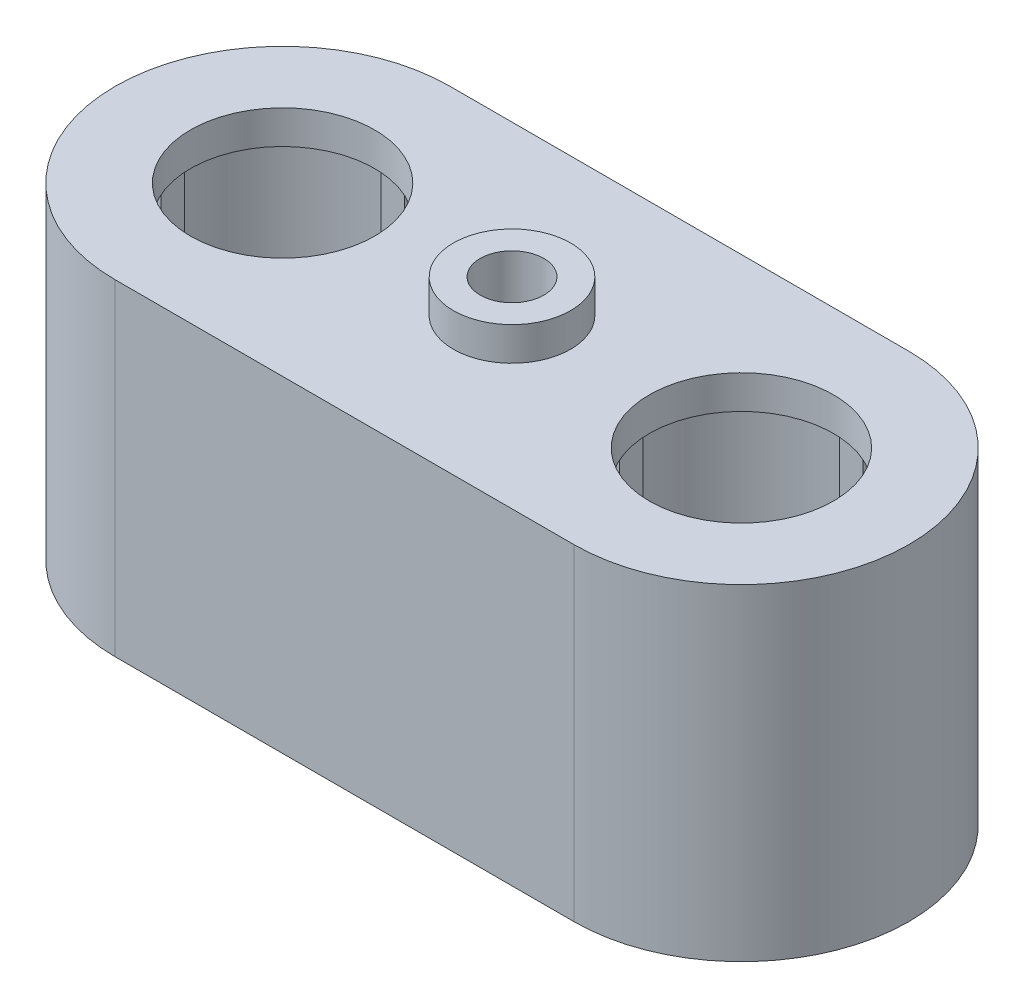
SolidWorks part; units mm, degrees
ref_plane "Front Plane" through (0, 0, 0) normal (0, 0, 1) x (1, 0, 0)
ref_plane "Top Plane" through (0, 0, 0) normal (0, 1, 0) x (1, 0, 0)
ref_plane "Right Plane" through (0, 0, 0) normal (1, 0, 0) x (0, 0, -1)
sketch "Sketch1" plane through (0, 0, 0) normal (0, 1, 0) x (1, 0, 0)
  line L3 (2.25, 5) -> (-2.25, 5)
  line L6 (2.35, -5) -> (-2.35, -5)
  line L16 (-1043.8651, 0) -> (-45, 0) construction
  line L17 (-2.25, 5) -> (-6.85, 5)
  line L18 (2.25, 5) -> (6.85, 5)
  line L19 (-2.35, -5) -> (-6.85, -5)
  line L20 (2.35, -5) -> (6.85, -5)
  line L21 (0, 0) -> (0, -10) construction
  line L28 (-1.85, 0) -> (1.85, 0) construction
  line L29 (45, 0) -> (1043.8651, 0) construction
  circle A0 centre (0, 0) radius 45 construction
  circle A18 centre (0, 0) radius 0.95
  arc A23 (-6.85, -5) -> (-6.85, 5) centre (-6.85, 0) ccw construction
  arc A28 (6.85, 5) -> (6.85, -5) centre (6.85, 0) ccw construction
  arc A30 (6.85, 5) -> (6.85, -5) centre (6.85, 0) ccw
  arc A31 (-6.85, -5) -> (-6.85, 5) centre (-6.85, 0) ccw
  dimension "D1" = 90
  dimension "D2" = 6.85
  dimension "D5" = 10
  dimension "D9" = 1.9
  dimension "D7" = 10
  dimension "D6" = 6.85
extrude "Boss-Extrude1" add sketch "Sketch1" along normal blind 2.5
sketch "Sketch2" plane through (0, 0, 0) normal (0, 1, 0) x (1, 0, 0)
  line L0 (0, 0) -> (-6.85, 0) construction
  line L1 (-13.4792, 0.75) -> (-11.7934, 0.75)
  line L2 (-13.4792, -0.75) -> (-11.7934, -0.75)
  line L3 (-12.5007, -0.75) -> (-12.5007, 0.75) construction
  line L4 (-17.25, 0) -> (0.95, 0) construction
  line L5 (-7.2, 3.9847) -> (-7.2, 3.2847)
  line L6 (-6.5, 3.9847) -> (-6.5, 3.2847)
  line L7 (-6.85, 0) -> (-6.85, 4) construction
  line L9 (-7.2, 3.2847) -> (-6.5, 3.2847)
  line L10 (-3.5653, 0.35) -> (-3.5653, -0.35)
  line L11 (-2.8653, 0.35) -> (-3.5653, 0.35)
  line L12 (-2.8653, -0.35) -> (-3.5653, -0.35)
  line L13 (-6.5, -3.2847) -> (-7.2, -3.2847)
  line L14 (-6.5, -3.9847) -> (-6.5, -3.2847)
  line L15 (-7.2, -3.9847) -> (-7.2, -3.2847)
  line L16 (-10.1347, -0.35) -> (-10.1347, 0.35)
  line L17 (-10.8347, -0.35) -> (-10.1347, -0.35)
  line L18 (-10.8347, 0.35) -> (-10.1347, 0.35)
  line L42 (-6.85, 5) -> (6.85, 5)
  line L43 (-6.85, -5) -> (6.85, -5)
  line L44 (-3.85, 4) -> (3.85, 4)
  line L45 (-7.2, 3.9847) -> (-6.5, 3.9847) construction
  line L46 (-3.85, -4) -> (3.85, -4)
  line L47 (-6.85, -4) -> (6.75, -4) construction
  line L48 (6.5, 3.9847) -> (6.5, 3.2847)
  line L49 (6.5, 3.2847) -> (7.2, 3.2847)
  line L50 (7.2, 3.9847) -> (7.2, 3.2847)
  line L51 (10.8347, 0.35) -> (10.1347, 0.35)
  line L52 (11.75, 0) -> (16.25, 0) construction
  line L53 (10.1347, 0.35) -> (10.1347, -0.35)
  line L54 (10.8347, -0.35) -> (10.1347, -0.35)
  line L55 (7.2, -3.9847) -> (7.2, -3.2847)
  line L56 (7.2, -3.2847) -> (6.5, -3.2847)
  line L57 (6.5, -3.9847) -> (6.5, -3.2847)
  line L58 (2.8653, -0.35) -> (3.5653, -0.35)
  line L59 (3.5653, -0.35) -> (3.5653, 0.35)
  line L60 (2.8653, 0.35) -> (3.5653, 0.35)
  line L61 (-6.85, -5) -> (6.75, -5) construction
  arc A2 (-1.8922, -0.6479) -> (1.8922, -0.6479) centre (0, 0) ccw
  circle A3 centre (0, 0) radius 0.95
  arc A4 (-6.85, 5) -> (-6.85, -5) centre (-6.85, 0) ccw
  arc A5 (-10.8347, -0.35) -> (-7.2, -3.9847) centre (-6.85, 0) ccw
  arc A6 (-6.5, -3.9847) -> (-2.8653, -0.35) centre (-6.85, 0) ccw
  arc A7 (-2.8653, 0.35) -> (-6.5, 3.9847) centre (-6.85, 0) ccw
  arc A8 (-7.2, 3.9847) -> (-10.8347, 0.35) centre (-6.85, 0) ccw
  arc A15 (-1.8922, 0.6479) -> (-3.85, 4) centre (-6.85, 0) ccw
  arc A16 (-1.8922, -0.6479) -> (1.8922, -0.6479) centre (0, 0) ccw
  arc A22 (-6.85, 5) -> (-6.85, -5) centre (-6.85, 0) ccw
  arc A23 (-3.85, -4) -> (-1.8922, -0.6479) centre (-6.85, 0) ccw
  arc A24 (-3.85, -4) -> (-1.8922, -0.6479) centre (-6.85, 0) ccw
  arc A25 (10.8347, 0.35) -> (7.2, 3.9847) centre (6.85, 0) ccw
  arc A26 (-1.8922, 0.6479) -> (-3.85, 4) centre (-6.85, 0) ccw
  arc A27 (7.2, -3.9847) -> (10.8347, -0.35) centre (6.85, 0) ccw
  arc A28 (1.8922, 0.6479) -> (-1.8922, 0.6479) centre (0, 0) ccw
  arc A29 (1.8922, 0.6479) -> (-1.8922, 0.6479) centre (0, 0) ccw
  arc A30 (2.8653, -0.35) -> (6.5, -3.9847) centre (6.85, 0) ccw
  arc A31 (6.5, 3.9847) -> (2.8653, 0.35) centre (6.85, 0) ccw
  arc A32 (6.85, -5) -> (6.85, 5) centre (6.85, 0) ccw
  arc A33 (1.8922, -0.6479) -> (3.85, -4) centre (6.85, 0) ccw
  arc A34 (3.85, 4) -> (1.8922, 0.6479) centre (6.85, 0) ccw
  point P15 (-12.5007, 0)
  point P22 (-6.85, 2)
  point P24 (-6.85, 0)
  dimension "D2" = 2
  dimension "D4" = 1.9
  dimension "D5" = 10
  dimension "D6" = 1
  dimension "D7" = 6.85
  dimension "D8" = 1.5
  dimension "D9" = 0.7
  dimension "D10" = 0.7
  dimension "D12" = 1
  dimension "D11" = 4
extrude "Boss-Extrude2" add sketch "Sketch2" along normal blind 9.75
sketch "Sketch3" plane through (0, 9.75, 0) normal (0, 1, 0) x (1, 0, 0)
  line L3 (-6.85, 5) -> (6.85, 5)
  line L4 (6.85, -5) -> (-6.85, -5)
  circle A1 centre (0, 0) radius 0.95
  arc A7 (-6.85, 5) -> (-6.85, -5) centre (-6.85, 0) ccw
  arc A8 (-6.85, 5) -> (-6.85, -5) centre (-6.85, 0) ccw construction
  arc A10 (6.85, 5) -> (6.85, -5) centre (6.85, 0) cw
  arc A11 (6.85, -5) -> (6.85, 5) centre (6.85, 0) ccw construction
  circle A12 centre (-6.85, 0) radius 2.75
  circle A13 centre (6.85, 0) radius 2.75
  dimension "D1" = 1.9
  dimension "D2" = 5.5
  dimension "D3" = 5.5
extrude "Boss-Extrude3" add sketch "Sketch3" against normal blind 1
sketch "Sketch4" plane through (0, 9.75, 0) normal (0, 1, 0) x (1, 0, 0)
  circle A0 centre (0, 0) radius 1.75
  circle A1 centre (0, 0) radius 0.95
  dimension "D1" = 3.5
  dimension "D2" = 1.9
extrude "Boss-Extrude4" add sketch "Sketch4" along normal blind 1
ref_plane "Plane1" through (11.85, 0, 0) normal (1, 0, 0) x (0, 0, -1)
